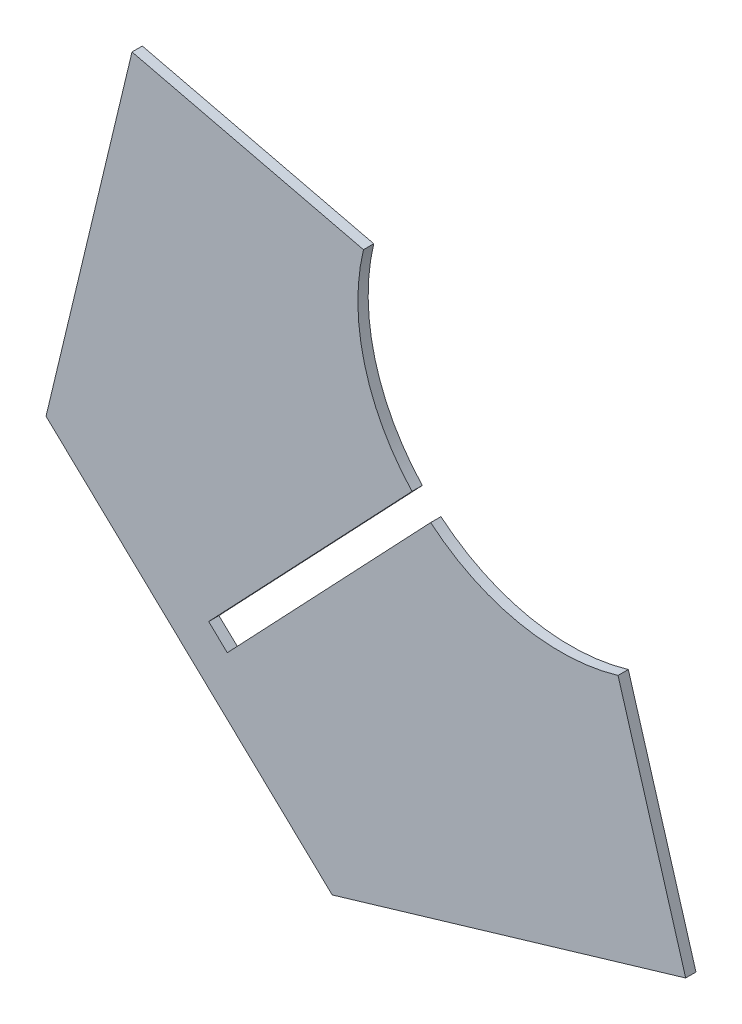
SolidWorks part; units mm, degrees
ref_plane "Plan de face" through (0, 0, 0) normal (0, 0, 1) x (1, 0, 0)
ref_plane "Plan de dessus" through (0, 0, 0) normal (0, 1, 0) x (1, 0, 0)
ref_plane "Plan de droite" through (0, 0, 0) normal (1, 0, 0) x (0, 0, -1)
sketch "Esquisse1" plane through (0, 0, 0) normal (0, 0, 1) x (1, 0, 0)
  line L0 (-0.2191, -0.231) -> (173.9748, 183.4224) construction
  line L1 (-0.2191, -0.231) -> (71.7325, -242.914) construction
  line L2 (-0.2191, -0.231) -> (-246.3646, 58.7986) construction
  line L3 (-57.9935, -53.8772) -> (-137.1335, -137.3149) construction
  line L5 (-107.9626, 101.9629) -> (-252.4792, -50.4017) construction
  line L6 (-107.9626, 101.9629) -> (107.5244, -102.4249) construction
  line L7 (107.5244, -102.4249) -> (-36.9922, -254.7894) construction
  line L8 (-252.4792, -50.4017) -> (-36.9922, -254.7894)
  line L9 (-57.6198, -68.0144) -> (-64.8752, -61.1327) construction
  line L10 (22.1916, -75.8191) -> (48.5227, -164.6306)
  line L11 (-76.8856, 18.1549) -> (-166.9643, 39.7571)
  line L12 (-36.9922, -254.7894) -> (48.5227, -164.6306)
  line L13 (-252.4792, -50.4017) -> (-166.9643, 39.7571)
  line L15 (-129.8781, -144.1967) -> (-137.1335, -137.3149) construction
  line L16 (-137.1335, -137.3149) -> (-57.9935, -53.8772)
  line L17 (-129.8781, -144.1967) -> (-137.1335, -137.3149)
  line L18 (-129.8781, -144.1967) -> (-50.738, -60.759)
  line L19 (-50.738, -60.759) -> (-57.9935, -53.8772) construction
  circle A1 centre (0, 0) radius 79 construction
  arc A2 (22.1916, -75.8191) -> (-50.738, -60.759) centre (-0.2191, -0.231) cw
  arc A3 (-76.8856, 18.1549) -> (-57.9935, -53.8772) centre (-0.2191, -0.231) ccw
  dimension "D1" = 120
  dimension "D2" = 120
  dimension "D3" = 297
  dimension "D4" = 210
extrude "Boss.-Extru.1" add sketch "Esquisse1" against normal blind 4
sketch "Esquisse3" plane through (0, 0, 0) normal (0, 0, 1) x (1, 0, 0)
  line L0 (-166.9643, 39.7571) -> (-200.426, -99.7737)
  line L1 (-252.4792, -50.4017) -> (-36.9922, -254.7894) construction
  line L2 (-200.426, -99.7737) -> (-252.4792, -50.4017)
  line L3 (-252.4792, -50.4017) -> (-166.9643, 39.7571)
  line L4 (-76.8856, 18.1549) -> (-166.9643, 39.7571) construction
  line L5 (-36.9922, -254.7894) -> (48.5227, -164.6306)
  line L6 (-36.9922, -254.7894) -> (48.5227, -164.6306) construction
  line L7 (48.5227, -164.6306) -> (-89.0454, -205.4174)
  line L8 (-89.0454, -205.4174) -> (-36.9922, -254.7894)
  line L9 (48.5227, -164.6306) -> (22.1916, -75.8191) construction
  point P14 (50.6305, -162.4084)
  point P16 (37.5529, -176.1961)
extrude "Enlèv. mat.-Extru.2" cut sketch "Esquisse3" against normal blind 10
